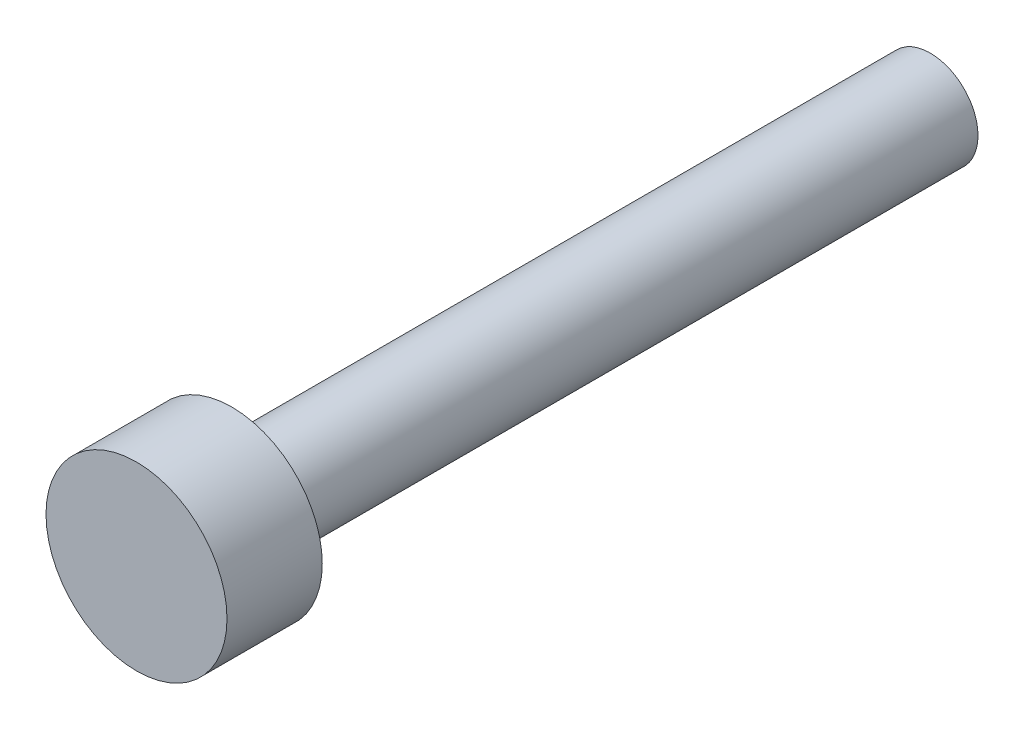
SolidWorks part; units mm, degrees
ref_plane "Front Plane" through (0, 0, 0) normal (0, 0, 1) x (1, 0, 0)
ref_plane "Top Plane" through (0, 0, 0) normal (0, 1, 0) x (1, 0, 0)
ref_plane "Right Plane" through (0, 0, 0) normal (1, 0, 0) x (0, 0, -1)
sketch "Sketch1" plane through (0, 0, 0) normal (0, 0, 1) x (1, 0, 0)
  circle A0 centre (0, 0) radius 1.5
  dimension "D1" = 3
extrude "Boss-Extrude1" add sketch "Sketch1" along normal blind 22
sketch "Sketch2" plane through (0, 0, 22) normal (0, 0, 1) x (1, 0, 0)
  circle A0 centre (0, 0) radius 2.85
  dimension "D1" = 5.7
extrude "Boss-Extrude2" add sketch "Sketch2" along normal blind 3
